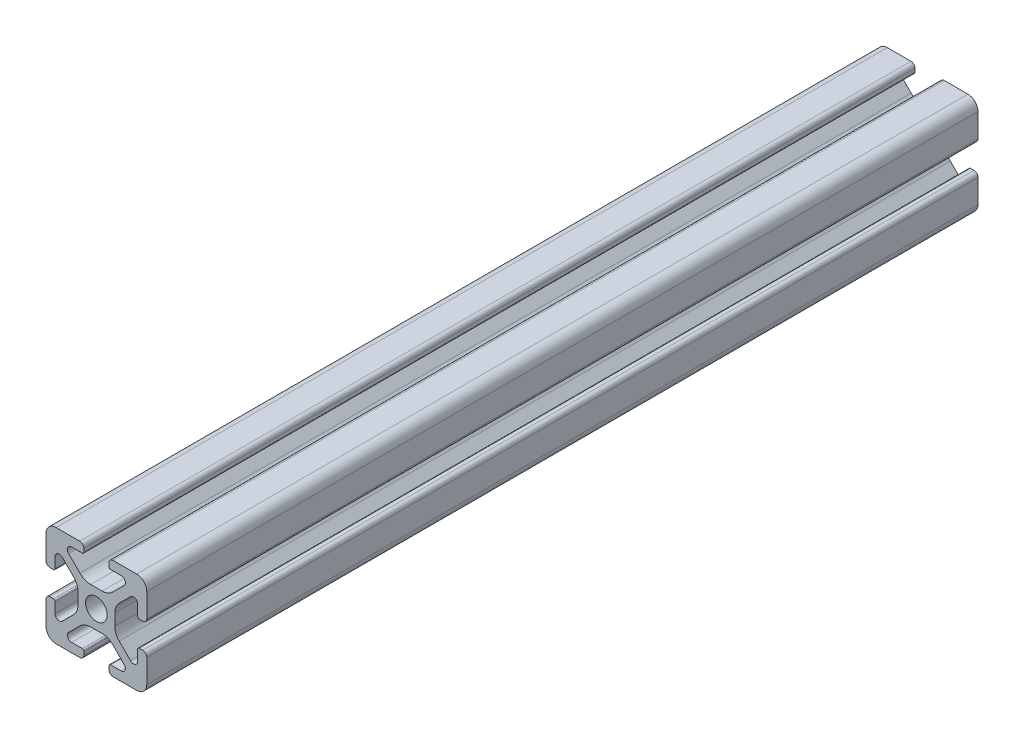
SolidWorks part; units mm, degrees
material "3.0205 (EN-AW 1200)"
ref_plane "Plan de face" through (0, 0, 0) normal (0, 0, 1) x (1, 0, 0)
ref_plane "Plan de dessus" through (0, 0, 0) normal (0, 1, 0) x (1, 0, 0)
ref_plane "Plan de droite" through (0, 0, 0) normal (1, 0, 0) x (0, 0, -1)
ref_plane "Plan1" through (0, 0, 0) normal (0, 0, -1) x (-1, 0, 0)
sketch "Esquisse1" plane through (0, 0, 0) normal (0, 0, -1) x (-1, 0, 0)
  line L0 (-12.5, 0.8) -> (-12.5, 1.5)
  line L1 (-12.8, 1.8) -> (-14.9176, 1.8)
  line L2 (-15.5062, 3.221) -> (-13.2559, 5.4713)
  line L3 (-11.1346, 6.35) -> (-8.8654, 6.35)
  line L4 (-6.7441, 5.4713) -> (-4.4938, 3.221)
  line L5 (-5.0824, 1.8) -> (-7.2, 1.8)
  line L6 (-7.5, 1.5) -> (-7.5, 0.8)
  line L7 (-6.7, 0) -> (-2, 0)
  line L8 (0, 2) -> (0, 6.7)
  line L9 (-0.8, 7.5) -> (-1.5, 7.5)
  line L10 (-1.8, 7.2) -> (-1.8, 5.0824)
  line L11 (-3.221, 4.4938) -> (-5.4713, 6.7441)
  line L12 (-6.35, 8.8654) -> (-6.35, 11.1346)
  line L13 (-5.4713, 13.2559) -> (-3.221, 15.5062)
  line L14 (-1.8, 14.9176) -> (-1.8, 12.8)
  line L15 (-1.5, 12.5) -> (-0.8, 12.5)
  line L16 (0, 13.3) -> (0, 18)
  line L17 (-2, 20) -> (-6.7, 20)
  line L18 (-7.5, 19.2) -> (-7.5, 18.5)
  line L19 (-7.2, 18.2) -> (-5.0824, 18.2)
  line L20 (-4.4938, 16.779) -> (-6.7441, 14.5287)
  line L21 (-8.8654, 13.65) -> (-11.1346, 13.65)
  line L22 (-13.2559, 14.5287) -> (-15.5062, 16.779)
  line L23 (-14.9176, 18.2) -> (-12.8, 18.2)
  line L24 (-12.5, 18.5) -> (-12.5, 19.2)
  line L25 (-13.3, 20) -> (-18, 20)
  line L26 (-20, 18) -> (-20, 13.3)
  line L27 (-19.2, 12.5) -> (-18.5, 12.5)
  line L28 (-18.2, 12.8) -> (-18.2, 14.9176)
  line L29 (-16.779, 15.5062) -> (-14.5287, 13.2559)
  line L30 (-13.65, 11.1346) -> (-13.65, 8.8654)
  line L31 (-14.5287, 6.7441) -> (-16.779, 4.4938)
  line L32 (-18.2, 5.0824) -> (-18.2, 7.2)
  line L33 (-18.5, 7.5) -> (-19.2, 7.5)
  line L34 (-20, 6.7) -> (-20, 2)
  line L35 (-18, 0) -> (-13.3, 0)
  arc A0 (-12.5, 1.5) -> (-12.8, 1.8) centre (-12.8, 1.5) ccw
  arc A1 (-14.9176, 1.8) -> (-15.5062, 3.221) centre (-14.9176, 2.6324) cw
  arc A2 (-13.2559, 5.4713) -> (-11.1346, 6.35) centre (-11.1346, 3.35) cw
  arc A3 (-8.8654, 6.35) -> (-6.7441, 5.4713) centre (-8.8654, 3.35) cw
  arc A4 (-4.4938, 3.221) -> (-5.0824, 1.8) centre (-5.0824, 2.6324) cw
  arc A5 (-7.2, 1.8) -> (-7.5, 1.5) centre (-7.2, 1.5) ccw
  arc A6 (-7.5, 0.8) -> (-6.7, 0) centre (-6.7, 0.8) ccw
  arc A7 (-2, 0) -> (0, 2) centre (-2, 2) ccw
  arc A8 (0, 6.7) -> (-0.8, 7.5) centre (-0.8, 6.7) ccw
  arc A9 (-1.5, 7.5) -> (-1.8, 7.2) centre (-1.5, 7.2) ccw
  arc A10 (-1.8, 5.0824) -> (-3.221, 4.4938) centre (-2.6324, 5.0824) cw
  arc A11 (-5.4713, 6.7441) -> (-6.35, 8.8654) centre (-3.35, 8.8654) cw
  arc A12 (-6.35, 11.1346) -> (-5.4713, 13.2559) centre (-3.35, 11.1346) cw
  arc A13 (-3.221, 15.5062) -> (-1.8, 14.9176) centre (-2.6324, 14.9176) cw
  arc A14 (-1.8, 12.8) -> (-1.5, 12.5) centre (-1.5, 12.8) ccw
  arc A15 (-0.8, 12.5) -> (0, 13.3) centre (-0.8, 13.3) ccw
  arc A16 (0, 18) -> (-2, 20) centre (-2, 18) ccw
  arc A17 (-6.7, 20) -> (-7.5, 19.2) centre (-6.7, 19.2) ccw
  arc A18 (-7.5, 18.5) -> (-7.2, 18.2) centre (-7.2, 18.5) ccw
  arc A19 (-5.0824, 18.2) -> (-4.4938, 16.779) centre (-5.0824, 17.3676) cw
  arc A20 (-6.7441, 14.5287) -> (-8.8654, 13.65) centre (-8.8654, 16.65) cw
  arc A21 (-11.1346, 13.65) -> (-13.2559, 14.5287) centre (-11.1346, 16.65) cw
  arc A22 (-15.5062, 16.779) -> (-14.9176, 18.2) centre (-14.9176, 17.3676) cw
  arc A23 (-12.8, 18.2) -> (-12.5, 18.5) centre (-12.8, 18.5) ccw
  arc A24 (-12.5, 19.2) -> (-13.3, 20) centre (-13.3, 19.2) ccw
  arc A25 (-18, 20) -> (-20, 18) centre (-18, 18) ccw
  arc A26 (-20, 13.3) -> (-19.2, 12.5) centre (-19.2, 13.3) ccw
  arc A27 (-18.5, 12.5) -> (-18.2, 12.8) centre (-18.5, 12.8) ccw
  arc A28 (-18.2, 14.9176) -> (-16.779, 15.5062) centre (-17.3676, 14.9176) cw
  arc A29 (-14.5287, 13.2559) -> (-13.65, 11.1346) centre (-16.65, 11.1346) cw
  arc A30 (-13.65, 8.8654) -> (-14.5287, 6.7441) centre (-16.65, 8.8654) cw
  arc A31 (-16.779, 4.4938) -> (-18.2, 5.0824) centre (-17.3676, 5.0824) cw
  arc A32 (-18.2, 7.2) -> (-18.5, 7.5) centre (-18.5, 7.2) ccw
  arc A33 (-19.2, 7.5) -> (-20, 6.7) centre (-19.2, 6.7) ccw
  arc A34 (-20, 2) -> (-18, 0) centre (-18, 2) ccw
  arc A35 (-13.3, 0) -> (-12.5, 0.8) centre (-13.3, 0.8) ccw
  circle A36 centre (-10, 10) radius 2.15
extrude "Boss.-Extru.1" add sketch "Esquisse1" against normal blind 165
